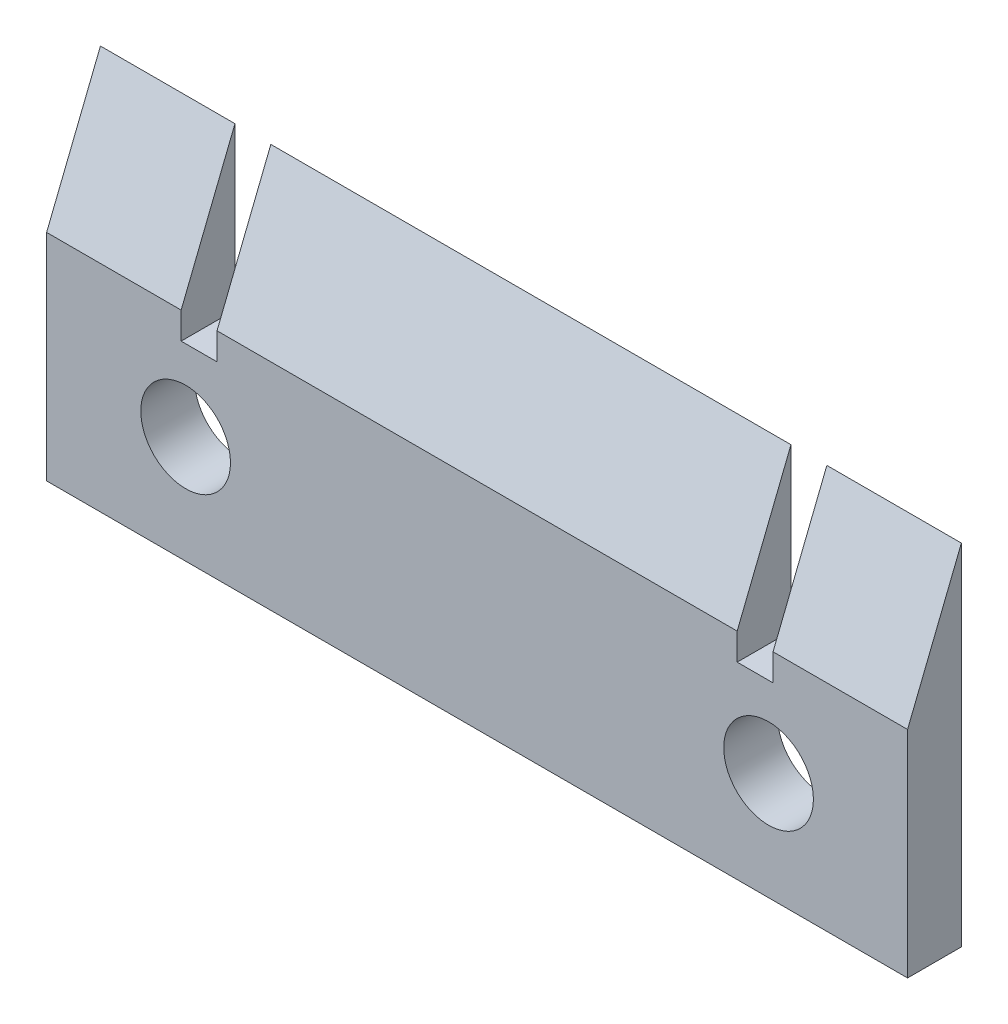
SolidWorks part; units mm, degrees
material "45钢"
ref_plane "前视基准面" through (0, 0, 0) normal (0, 0, 1) x (1, 0, 0)
ref_plane "上视基准面" through (0, 0, 0) normal (0, 1, 0) x (1, 0, 0)
ref_plane "右视基准面" through (0, 0, 0) normal (1, 0, 0) x (0, 0, -1)
sketch "草图1" plane through (0, 0, 0) normal (0, 0, 1) x (1, 0, 0)
  line L0 (0, -55) -> (0, 55) construction
  line L1 (-48, 39) -> (48, 39)
  line L2 (-48, 39) -> (-48, 0)
  line L3 (-48, 0) -> (48, 0)
  line L4 (48, 39) -> (48, 0)
  line L5 (-48, 39) -> (48, 0) construction
  line L6 (-48, 0) -> (48, 39) construction
  line L7 (55, 0) -> (-55, 0) construction
  point P0 (0, 19.5)
  dimension "D1" = 96
  dimension "D2" = 39
extrude "凸台-拉伸1" add sketch "草图1" along normal blind 6
sketch "草图2" plane through (48, 0, 0) normal (1, 0, 0) x (0, 0, -1)
  line L0 (-6, 24) -> (0, 39)
  line L1 (-6, 0) -> (-6, 39) construction
  line L2 (0, 21.45) -> (0, -21.45) construction
  line L3 (-6, 39) -> (0, 39) construction
  line L4 (3.3, 0) -> (-3.3, 0) construction
  dimension "D1" = 24
extrude "切除-拉伸1" cut sketch "草图2" against normal through all and the other way through all
sketch "草图3" plane through (0, 0, 6) normal (0, 0, 1) x (1, 0, 0)
  line L0 (-33, 39) -> (-33, 21)
  line L1 (48, 39) -> (-48, 39) construction
  line L2 (3.3, 0) -> (-3.3, 0) construction
  line L3 (0, -3.3) -> (0, 3.3) construction
  dimension "D1" = 21
  dimension "D2" = 33
extrude "切除-拉伸-薄壁1" cut sketch "草图3" against normal through all and the other way through all thin thin type one direction reverse wall 4
mirror "镜向1" about plane through (0, 0, 0) normal (1, 0, 0) of "切除-拉伸-薄壁1"
sketch "草图4" plane through (0, 0, 6) normal (0, 0, 1) x (1, 0, 0)
  line L0 (-32.5, 12) -> (32.5, 12) construction
  line L2 (0, -3.3) -> (0, 3.3) construction
  line L3 (3.3, 0) -> (-3.3, 0) construction
  circle A0 centre (32.5, 12) radius 5
  circle A1 centre (-32.5, 12) radius 5
  point P3 (0, 12)
  dimension "D3" = 10
  dimension "D4" = 10
  dimension "D1" = 65
  dimension "D2" = 12
extrude "切除-拉伸2" cut sketch "草图4" against normal through all
